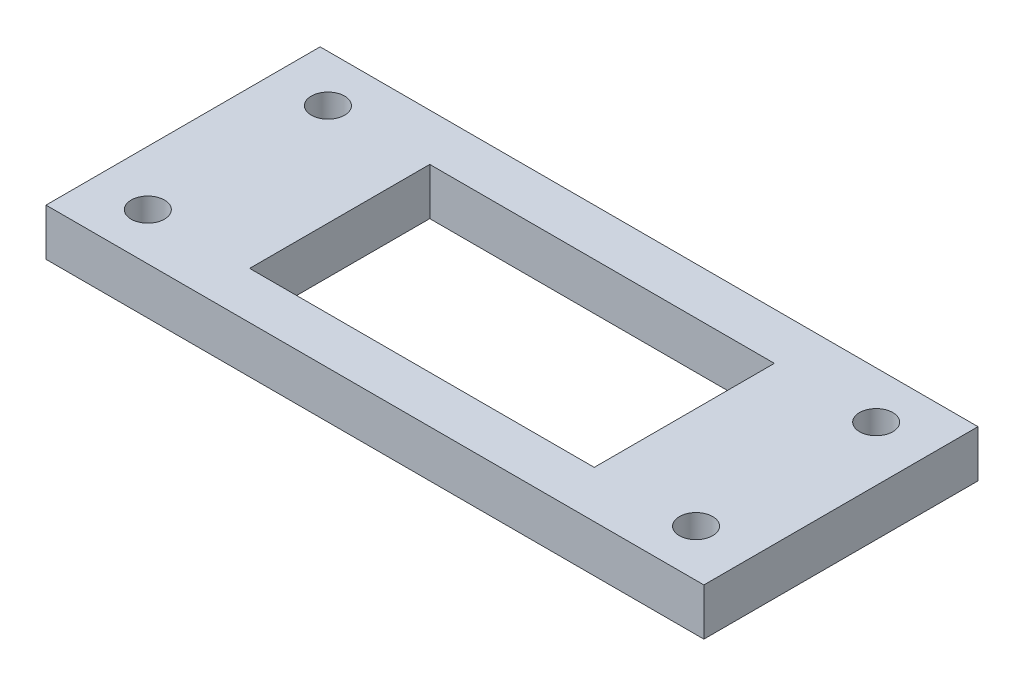
SolidWorks part; units mm, degrees
ref_plane "Front Plane" through (0, 0, 0) normal (0, 0, 1) x (1, 0, 0)
ref_plane "Top Plane" through (0, 0, 0) normal (0, 1, 0) x (1, 0, 0)
ref_plane "Right Plane" through (0, 0, 0) normal (1, 0, 0) x (0, 0, -1)
sketch "Sketch1" plane through (0, 0, 0) normal (0, 1, 0) x (1, 0, 0)
  line L1 (-84, -35) -> (84, -35)
  line L2 (-84, -35) -> (-84, 35)
  line L3 (-84, 35) -> (84, 35)
  line L4 (84, -35) -> (84, 35)
  line L5 (-44, -23) -> (44, -23)
  line L6 (-44, -23) -> (-44, 23)
  line L7 (-44, 23) -> (44, 23)
  line L8 (44, -23) -> (44, 23)
  circle A0 centre (-70, -23) radius 4.25
  circle A1 centre (70, -23) radius 4.25
  circle A2 centre (-70, 23) radius 4.25
  circle A3 centre (70, 23) radius 4.25
extrude "Bridge_Clamp_Extrude" add sketch "Sketch1" along normal blind 12
equation "\"ValveDiameter\" = 63mm"
equation "\"MotorGearTeeth\" = 40"
equation "\"OutputGearTeeth\" = 80"
equation "\"GearModule\" = 1.5mm"
equation "\"PressureAngle\" = 20deg"
equation "\"GearCenterDistance\" = 90mm"
equation "\"GearWidth\" = 18mm"
equation "\"OutputShaftDiameter\" = 20mm"
equation "\"BearingOD\" = 47mm"
equation "\"BearingWidth\" = 14mm"
equation "\"PlateThickness\" = 6mm"
equation "\"ValveRotation\" = 90deg"
